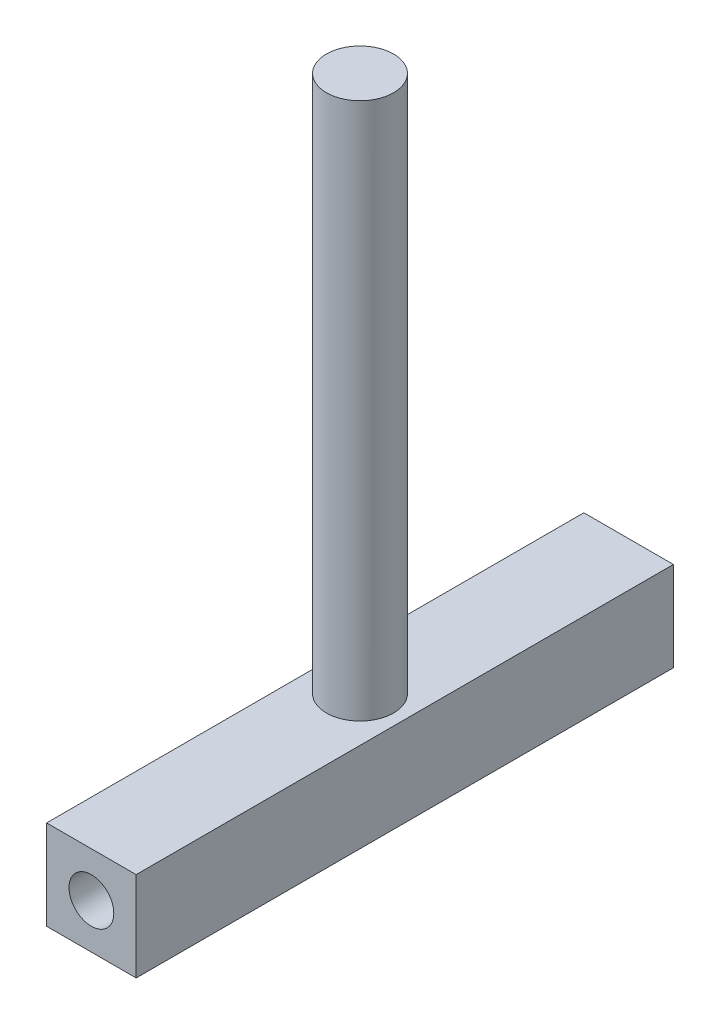
SolidWorks part; units mm, degrees
ref_plane "Front Plane" through (0, 0, 0) normal (0, 0, 1) x (1, 0, 0)
ref_plane "Top Plane" through (0, 0, 0) normal (0, 1, 0) x (1, 0, 0)
ref_plane "Right Plane" through (0, 0, 0) normal (1, 0, 0) x (0, 0, -1)
sketch "Sketch1" plane through (0, 0, 0) normal (0, 0, 1) x (1, 0, 0)
  line L1 (-10, 10) -> (10, 10)
  line L2 (-10, 10) -> (-10, -10)
  line L3 (-10, -10) -> (10, -10)
  line L4 (10, 10) -> (10, -10)
  line L5 (-10, 10) -> (10, -10) construction
  line L6 (-10, -10) -> (10, 10) construction
  circle A0 centre (0, 0) radius 5
  point P1 (0, 0)
  dimension "D3" = 10
  dimension "D1" = 20
  dimension "D2" = 20
extrude "Boss-Extrude1" add sketch "Sketch1" along normal blind 120
sketch "Sketch2" plane through (0, 10, 0) normal (0, 1, 0) x (1, 0, 0)
  line L0 (0, -120) -> (0, 0) construction
  line L1 (10, -120) -> (-10, -120) construction
  line L2 (-10, -60) -> (10, -60) construction
  line L3 (-10, -120) -> (-10, 0) construction
  line L4 (10, -120) -> (10, 0) construction
  circle A0 centre (0, -60) radius 7.5
  dimension "D1" = 15
extrude "Boss-Extrude2" add sketch "Sketch2" along normal blind 120
